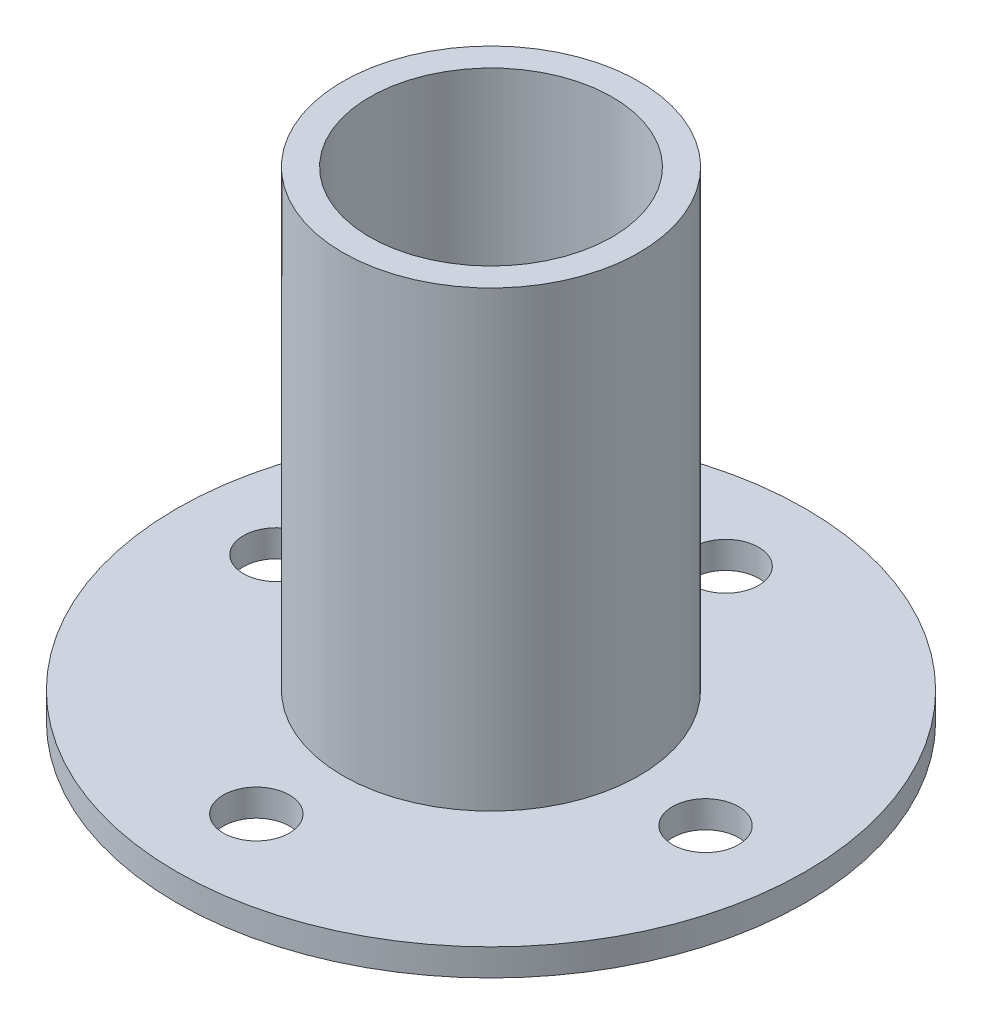
SolidWorks part; units mm, degrees
material "AISI 304"
ref_plane "Front" through (0, 0, 0) normal (0, 0, 1) x (1, 0, 0)
ref_plane "Top" through (0, 0, 0) normal (0, 1, 0) x (1, 0, 0)
ref_plane "Right" through (0, 0, 0) normal (1, 0, 0) x (0, 0, -1)
sketch "Sketch1" plane through (0, 0, 0) normal (0, 1, 0) x (1, 0, 0)
  circle A0 centre (0, 0) radius 35
  dimension "D1" = 70
extrude "Boss-Extrude1" add sketch "Sketch1" along normal blind 3
sketch "Sketch2" plane through (0, 3, 0) normal (0, 1, 0) x (1, 0, 0)
  circle A0 centre (0, 0) radius 14
  dimension "D1" = 28
extrude "Cut-Extrude1" cut sketch "Sketch2" against normal blind 6
sketch "Sketch3" plane through (0, 3, 0) normal (0, 1, 0) x (1, 0, 0)
  circle A0 centre (1.1195, 25) radius 3.6761
  dimension "D1" = 25
extrude "Cut-Extrude2" cut sketch "Sketch3" against normal blind 6
pattern_circular "CirPattern1" count 4 every 90 about axis through (0, 0, 0) along (0, 1, 0) of "Cut-Extrude2"
sketch "Sketch4" plane through (0, 3, 0) normal (0, 1, 0) x (1, 0, 0)
  circle A0 centre (0, 0) radius 16.5
  dimension "D1" = 33
extrude "Extrude-Thin1" add sketch "Sketch4" along normal blind 50.43 separate body thin thin type one direction reverse wall 3
